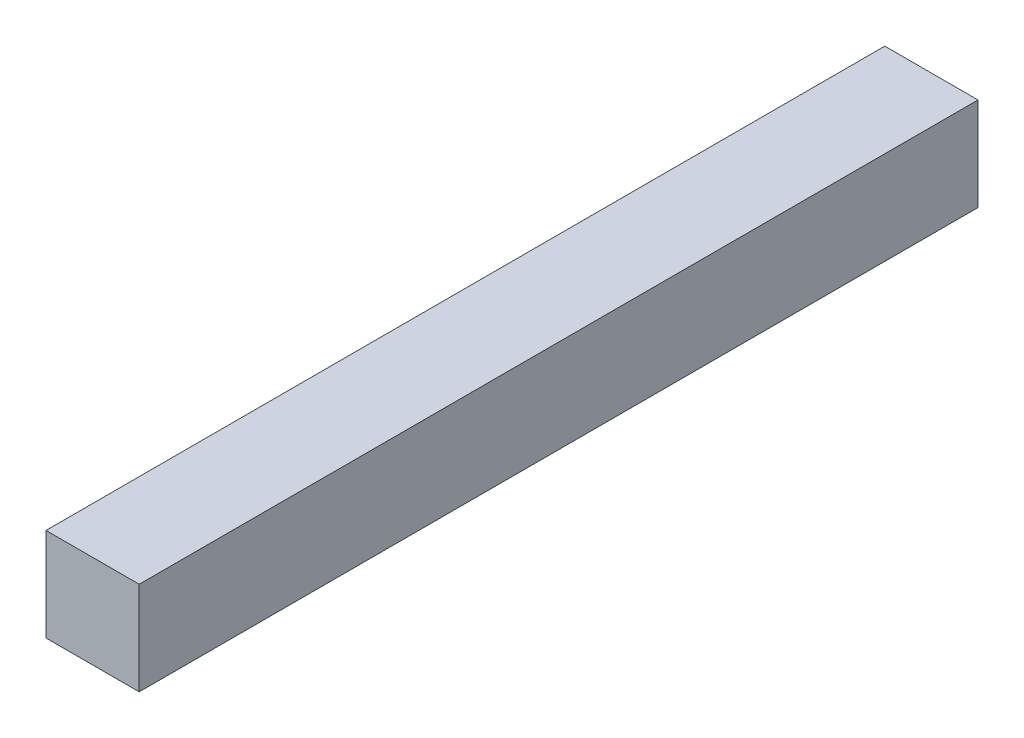
SolidWorks part; units mm, degrees
ref_plane "Front" through (0, 0, 0) normal (0, 0, 1) x (1, 0, 0)
ref_plane "Top" through (0, 0, 0) normal (0, 1, 0) x (1, 0, 0)
ref_plane "Right" through (0, 0, 0) normal (1, 0, 0) x (0, 0, -1)
sketch "Sketch2" plane through (0, 0, 0) normal (0, 0, 1) x (1, 0, 0)
  line L1 (0, 0) -> (-2.54, 0)
  line L2 (0, 0) -> (0, 2.54)
  line L3 (0, 2.54) -> (-2.54, 2.54)
  line L4 (-2.54, 0) -> (-2.54, 2.54)
  dimension "D1" = 2.54
extrude "Boss-Extrude1" add sketch "Sketch2" along normal blind 22.86
